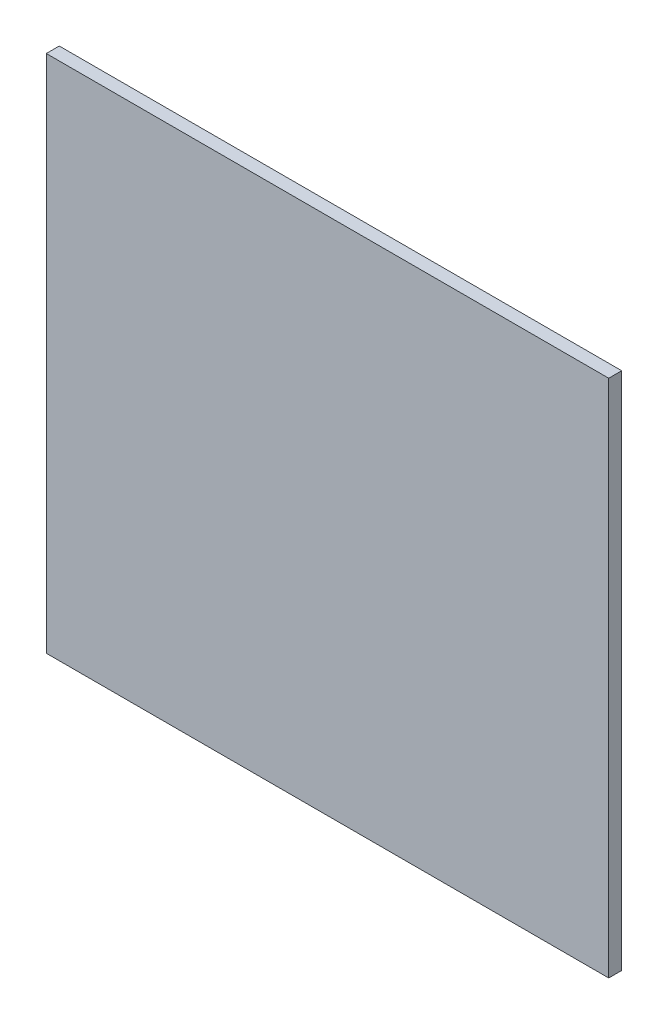
SolidWorks part; units mm, degrees
ref_plane "Front Plane" through (0, 0, 0) normal (0, 0, 1) x (1, 0, 0)
ref_plane "Top Plane" through (0, 0, 0) normal (0, 1, 0) x (1, 0, 0)
ref_plane "Right Plane" through (0, 0, 0) normal (1, 0, 0) x (0, 0, -1)
sketch "Sketch1" plane through (0, 0, 0) normal (0, 0, 1) x (1, 0, 0)
  line L1 (-68.7578, -63.5) -> (68.7578, -63.5)
  line L2 (-68.7578, -63.5) -> (-68.7578, 63.5)
  line L3 (-68.7578, 63.5) -> (68.7578, 63.5)
  line L4 (68.7578, -63.5) -> (68.7578, 63.5)
  line L5 (-68.7578, -63.5) -> (68.7578, 63.5) construction
  line L6 (-68.7578, 63.5) -> (68.7578, -63.5) construction
  point P0 (0, 0)
  dimension "D1" = 137.5156
  dimension "D2" = 127
extrude "Boss-Extrude1" add sketch "Sketch1" along normal blind 3.175
